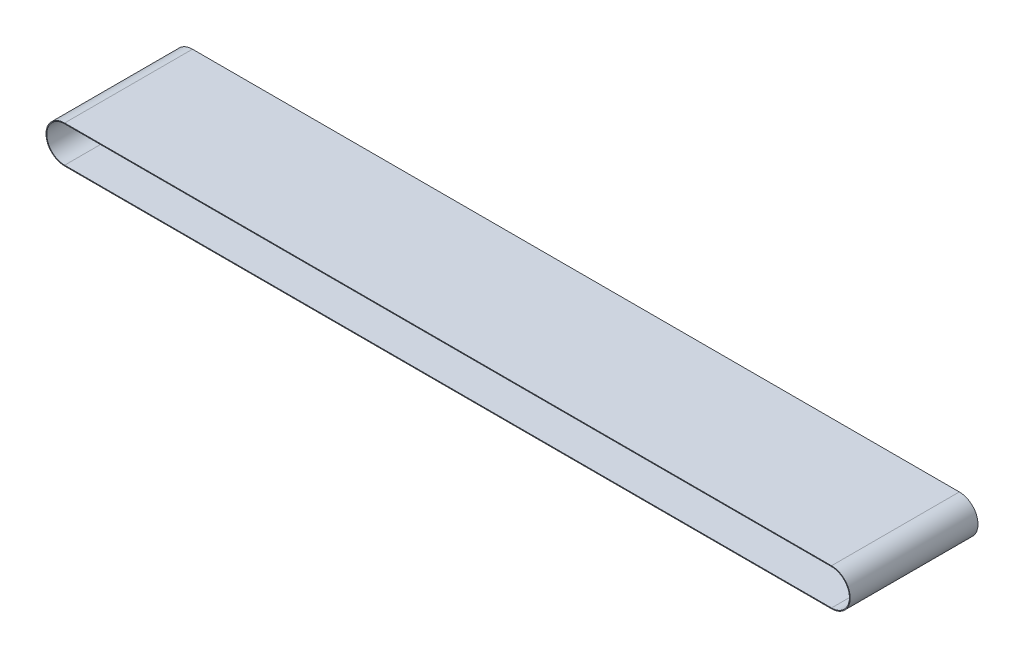
SolidWorks part; units mm, degrees
ref_plane "Ön Düzlem" through (0, 0, 0) normal (0, 0, 1) x (1, 0, 0)
ref_plane "Üst Düzlem" through (0, 0, 0) normal (0, 1, 0) x (1, 0, 0)
ref_plane "Sağ Düzlem" through (0, 0, 0) normal (1, 0, 0) x (0, 0, -1)
sketch "Çizim1" plane through (0, 0, 0) normal (0, 0, 1) x (1, 0, 0)
  line L0 (-1500, 0) -> (1500, 0) construction
  line L1 (-1500, 70) -> (1500, 70)
  line L2 (-1500, -70) -> (1500, -70)
  line L3 (-1500, 73) -> (1500, 73)
  line L4 (-1500, -73) -> (1500, -73)
  arc A0 (-1500, 70) -> (-1500, -70) centre (-1500, 0) ccw
  arc A1 (1500, -70) -> (1500, 70) centre (1500, 0) ccw
  arc A2 (1500, -73) -> (1500, 73) centre (1500, 0) ccw
  arc A3 (-1500, 73) -> (-1500, -73) centre (-1500, 0) ccw
  point P3 (0, 0)
  dimension "D2" = 70
  dimension "D1" = 3000
  dimension "D3" = 3
extrude "Yükseklik-Ekstrüzyon1" add sketch "Çizim1" along normal blind 500
